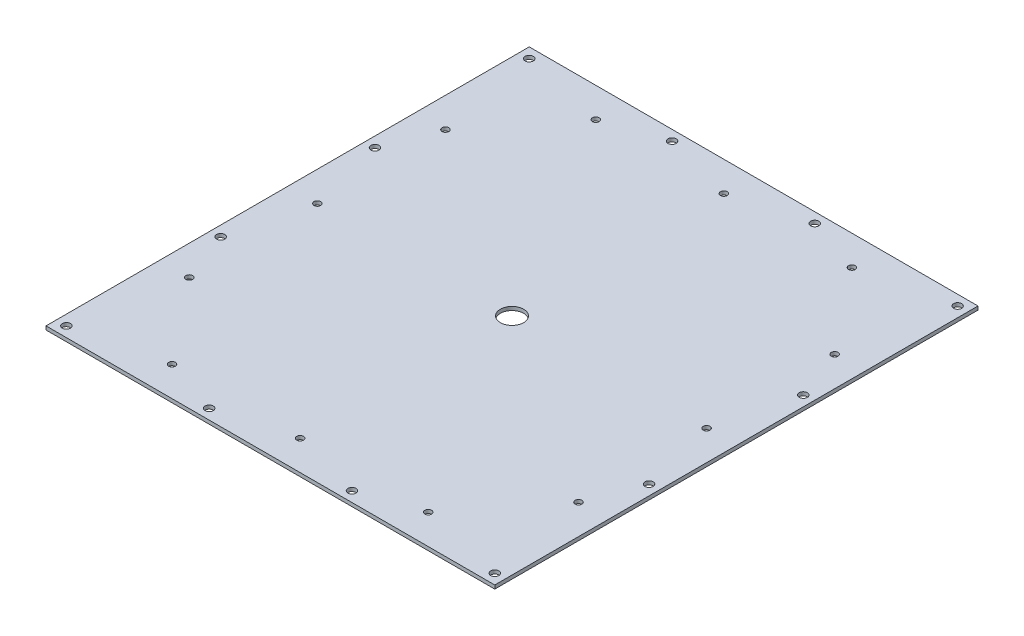
SolidWorks part; units mm, degrees
ref_plane "Front Plane" through (0, 0, 0) normal (0, 0, 1) x (1, 0, 0)
ref_plane "Top Plane" through (0, 0, 0) normal (0, 1, 0) x (1, 0, 0)
ref_plane "Right Plane" through (0, 0, 0) normal (1, 0, 0) x (0, 0, -1)
sketch "Sketch2" plane through (0, 0, 0) normal (0, 1, 0) x (1, 0, 0)
  line L0 (-8.89, -8.89) -> (186.8932, -8.89)
  line L1 (186.8932, -8.89) -> (186.8932, 201.93)
  line L2 (186.8932, 201.93) -> (-8.89, 201.93)
  line L3 (-8.89, 201.93) -> (-8.89, -8.89)
  circle A0 centre (-4.445, -4.445) radius 1.778
  circle A1 centre (-4.445, 197.485) radius 1.778
  circle A2 centre (-4.445, 62.865) radius 1.778
  circle A3 centre (-4.445, 130.175) radius 1.778
  circle A4 centre (57.8612, 197.485) radius 1.778
  circle A5 centre (120.142, 197.485) radius 1.778
  circle A6 centre (57.8612, -4.445) radius 1.778
  circle A7 centre (120.142, -4.445) radius 1.778
  circle A8 centre (182.4482, -4.445) radius 1.778
  circle A9 centre (182.4482, 197.485) radius 1.778
  circle A10 centre (182.4482, 62.865) radius 1.778
  circle A11 centre (182.4482, 130.175) radius 1.778
  circle A12 centre (33.1216, 4.0894) radius 1.4732
  circle A13 centre (89.0016, 4.0894) radius 1.4732
  circle A14 centre (144.8816, 4.0894) radius 1.4732
  circle A15 centre (33.1216, 188.9506) radius 1.4732
  circle A16 centre (89.0016, 188.9506) radius 1.4732
  circle A17 centre (144.8816, 188.9506) radius 1.4732
  circle A18 centre (4.0894, 40.64) radius 1.4732
  circle A19 centre (4.0894, 96.52) radius 1.4732
  circle A20 centre (4.0894, 152.4) radius 1.4732
  circle A21 centre (173.8884, 40.64) radius 1.4732
  circle A22 centre (173.8884, 96.52) radius 1.4732
  circle A23 centre (173.8884, 152.4) radius 1.4732
  circle A24 centre (89.0016, 96.52) radius 5.08
extrude "Boss-Extrude1" add sketch "Sketch2" along normal blind 1.5748
